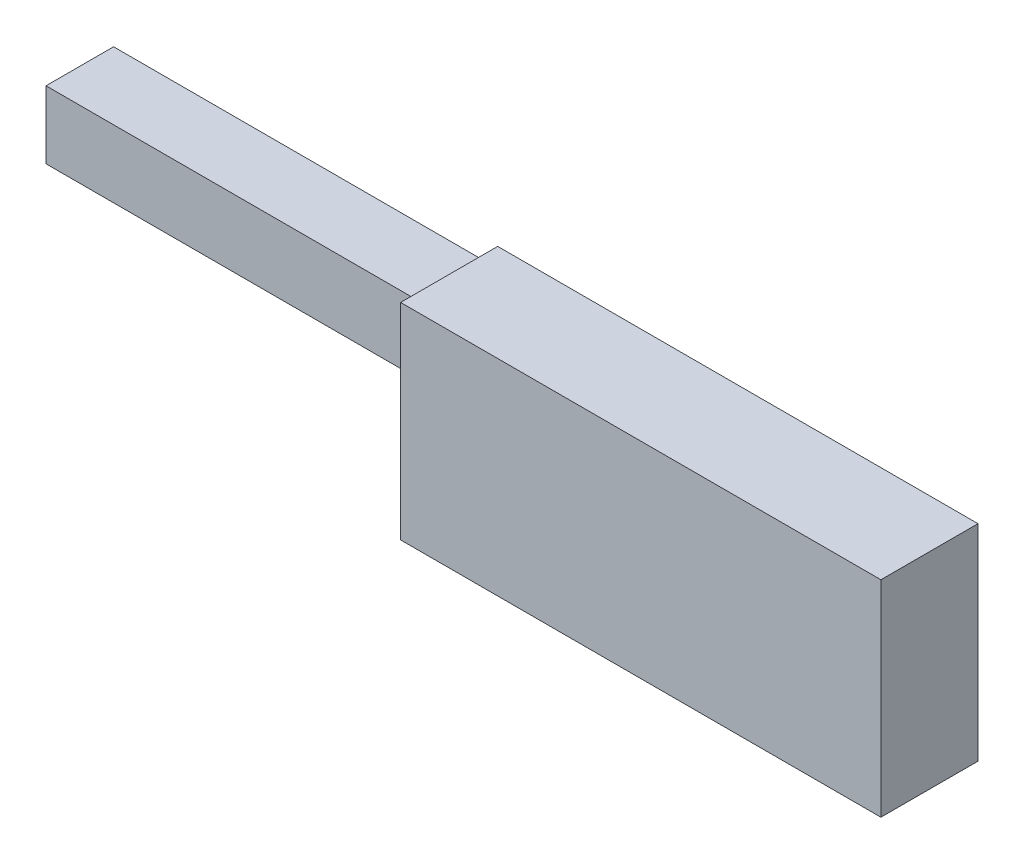
SolidWorks part; units mm, degrees
ref_plane "Plan de face" through (0, 0, 0) normal (0, 0, 1) x (1, 0, 0)
ref_plane "Plan de dessus" through (0, 0, 0) normal (0, 1, 0) x (1, 0, 0)
ref_plane "Plan de droite" through (0, 0, 0) normal (1, 0, 0) x (0, 0, -1)
sketch "Esquisse1" plane through (0, 0, 0) normal (0, 0, 1) x (1, 0, 0)
  line L1 (0, 0) -> (42.64, 0)
  line L2 (0, 0) -> (0, 18.26)
  line L3 (0, 18.26) -> (42.64, 18.26)
  line L4 (42.64, 0) -> (42.64, 18.26)
  dimension "D1" = 18.26
  dimension "D2" = 42.64
extrude "Boss.-Extru.1" add sketch "Esquisse1" along normal blind 8.62
sketch "Esquisse2" plane through (0, 0, 0) normal (-1, 0, 0) x (0, 0, 1)
  line L1 (1.0998, 17.6573) -> (7.0998, 17.6573)
  line L2 (1.0998, 17.6573) -> (1.0998, 11.6573)
  line L3 (1.0998, 11.6573) -> (7.0998, 11.6573)
  line L4 (7.0998, 17.6573) -> (7.0998, 11.6573)
  dimension "D1" = 6
extrude "Boss.-Extru.2" add sketch "Esquisse2" along normal blind 33
